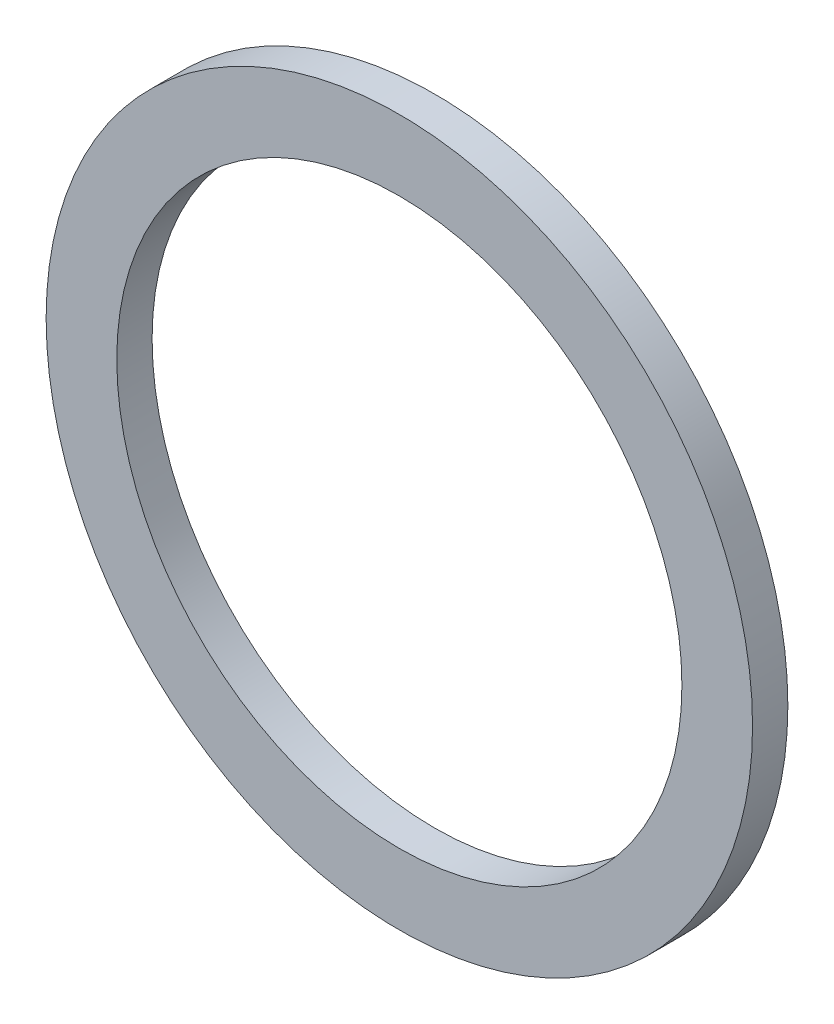
SolidWorks part; units mm, degrees
ref_plane "Front Plane" through (0, 0, 0) normal (0, 0, 1) x (1, 0, 0)
ref_plane "Top Plane" through (0, 0, 0) normal (0, 1, 0) x (1, 0, 0)
ref_plane "Right Plane" through (0, 0, 0) normal (1, 0, 0) x (0, 0, -1)
sketch "Sketch1" plane through (0, 0, 0) normal (0, 0, 1) x (1, 0, 0)
  circle A0 centre (0, 0) radius 10
  dimension "D1" = 20
extrude "Boss-Extrude1" add sketch "Sketch1" along normal blind 1
sketch "Sketch2" plane through (0, 0, 0) normal (0, 0, -1) x (-1, 0, 0)
  circle A0 centre (0, 0) radius 8
  dimension "D1" = 16
extrude "Cut-Extrude1" cut sketch "Sketch2" against normal through all both and the other way through all
